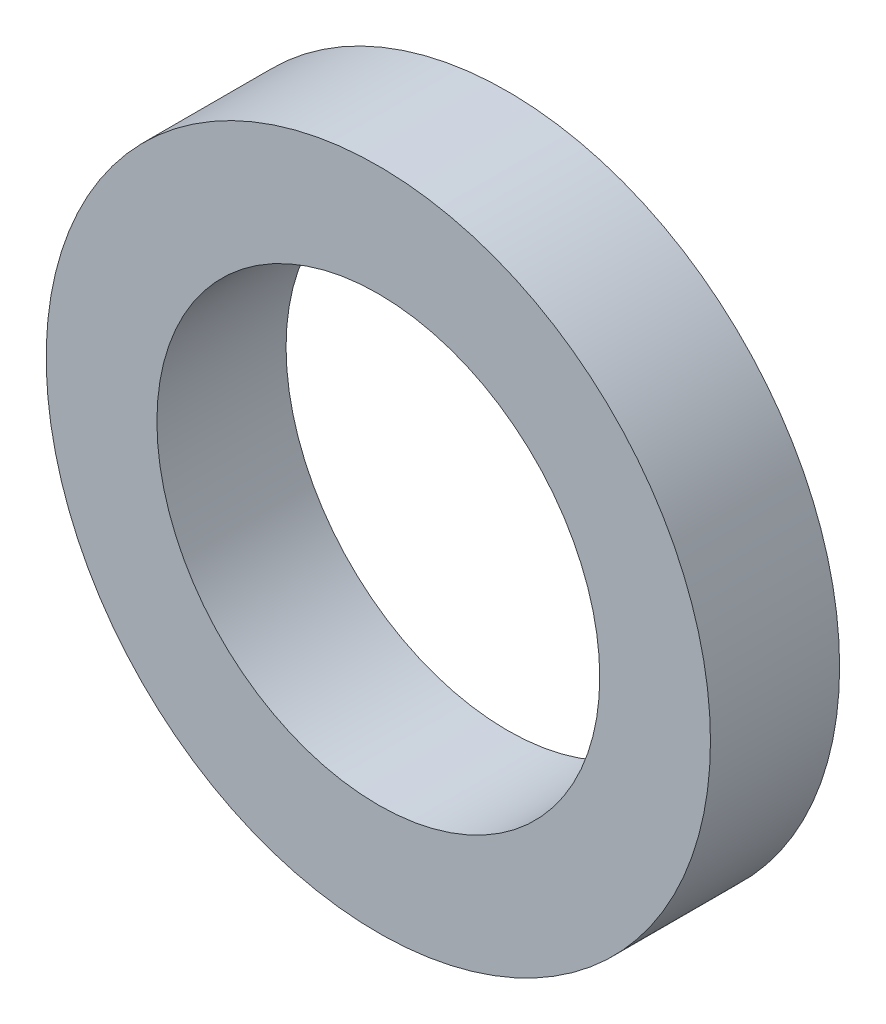
SolidWorks part; units mm, degrees
ref_plane "Front Plane" through (0, 0, 0) normal (0, 0, 1) x (1, 0, 0)
ref_plane "Top Plane" through (0, 0, 0) normal (0, 1, 0) x (1, 0, 0)
ref_plane "Right Plane" through (0, 0, 0) normal (1, 0, 0) x (0, 0, -1)
sketch "Sketch1" plane through (0, 0, 0) normal (0, 0, 1) x (1, 0, 0)
  circle A0 centre (0, 0) radius 18
  circle A1 centre (0, 0) radius 12
extrude "Upper sleeve - 24 ID and 36 OD" add sketch "Sketch1" along normal blind 7 from offset 58
